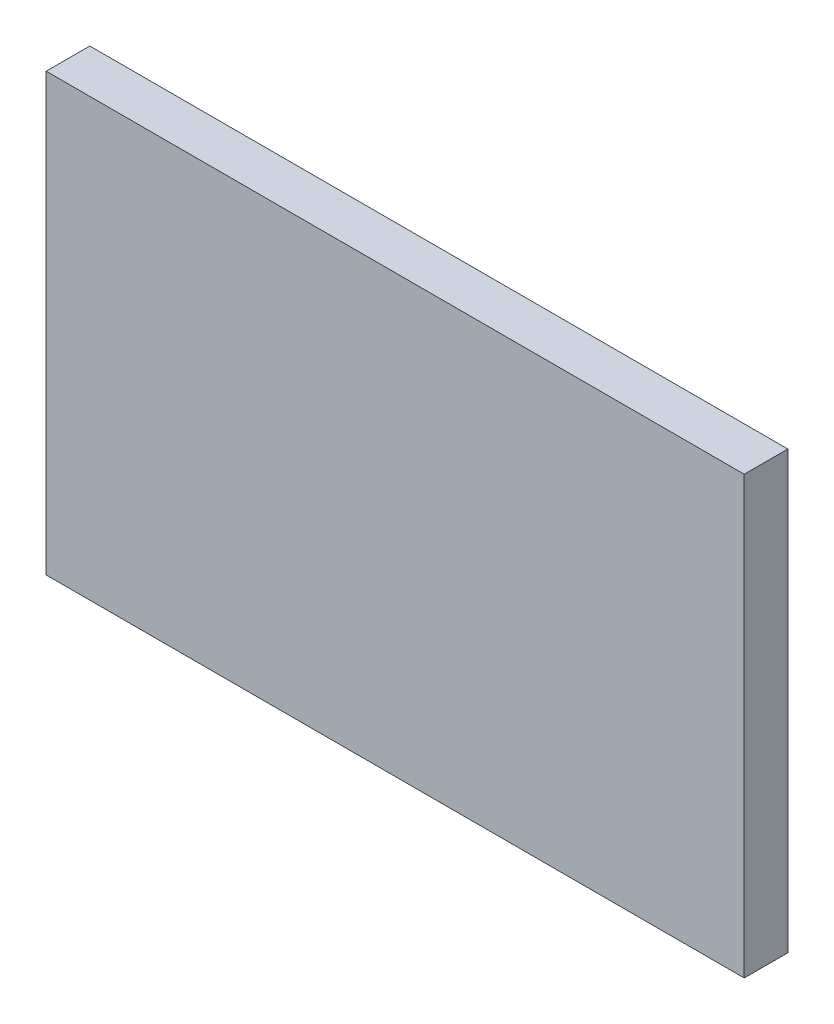
SolidWorks part; units mm, degrees
ref_plane "Front Plane" through (0, 0, 0) normal (0, 0, 1) x (1, 0, 0)
ref_plane "Top Plane" through (0, 0, 0) normal (0, 1, 0) x (1, 0, 0)
ref_plane "Right Plane" through (0, 0, 0) normal (1, 0, 0) x (0, 0, -1)
sketch "Sketch1" plane through (0, 0, 0) normal (0, 0, 1) x (1, 0, 0)
  line L1 (40, -25) -> (-40, -25)
  line L2 (40, -25) -> (40, 25)
  line L3 (40, 25) -> (-40, 25)
  line L4 (-40, -25) -> (-40, 25)
  line L5 (40, -25) -> (-40, 25) construction
  line L6 (40, 25) -> (-40, -25) construction
  point P0 (0, 0)
  dimension "D1" = 80
  dimension "D2" = 50
extrude "Boss-Extrude1" add sketch "Sketch1" along normal blind 5
